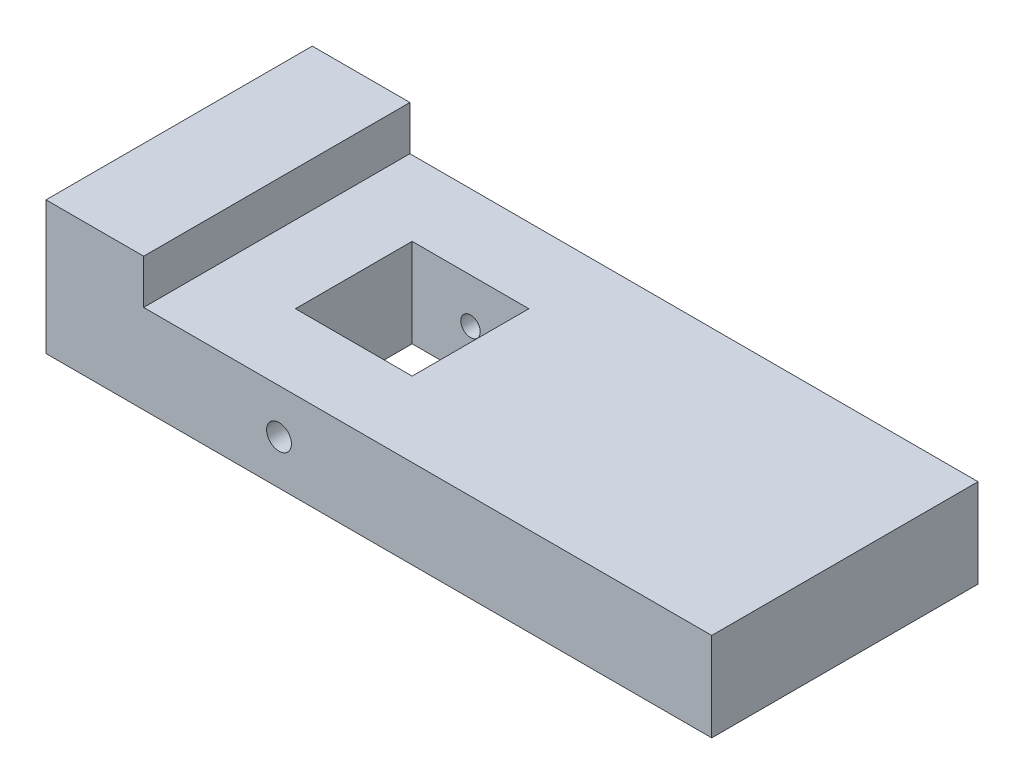
SolidWorks part; units mm, degrees
ref_plane "Front Plane" through (0, 0, 0) normal (0, 0, 1) x (1, 0, 0)
ref_plane "Top Plane" through (0, 0, 0) normal (0, 1, 0) x (1, 0, 0)
ref_plane "Right Plane" through (0, 0, 0) normal (1, 0, 0) x (0, 0, -1)
sketch "Sketch1" plane through (0, 0, 0) normal (0, 1, 0) x (1, 0, 0)
  line L1 (-75, -30) -> (75, -30)
  line L2 (-75, -30) -> (-75, 30)
  line L3 (-75, 30) -> (75, 30)
  line L4 (75, -30) -> (75, 30)
  line L5 (-75, -30) -> (75, 30) construction
  line L6 (-75, 30) -> (75, -30) construction
  point P0 (0, 0)
  dimension "D1" = 150
  dimension "D2" = 60
extrude "Boss-Extrude1" add sketch "Sketch1" along normal blind 20
sketch "Sketch2" plane through (0, 20, 0) normal (0, 1, 0) x (1, 0, 0)
  line L0 (-75, 30) -> (-75, -30) construction
  line L1 (-75, -30) -> (-53, -30)
  line L2 (-75, -30) -> (-75, 30)
  line L3 (-75, 30) -> (-53, 30)
  line L4 (-53, -30) -> (-53, 30)
  line L5 (-75, -30) -> (-53, 30) construction
  line L6 (-75, 30) -> (-53, -30) construction
  line L7 (75, 30) -> (-75, 30) construction
  point P0 (-64, 0)
  dimension "D1" = 22
  dimension "D2" = 60
  dimension "D3" = 0
  dimension "D4" = 0
extrude "Boss-Extrude2" add sketch "Sketch2" along normal blind 10
sketch "Sketch3" plane through (0, 20, 0) normal (0, 1, 0) x (1, 0, 0)
  line L0 (-53, -30) -> (75, -30) construction
  line L1 (-9.35, -13.15) -> (-35.65, -13.15)
  line L2 (-9.35, -13.15) -> (-9.35, 13.15)
  line L3 (-9.35, 13.15) -> (-35.65, 13.15)
  line L4 (-35.65, -13.15) -> (-35.65, 13.15)
  line L5 (-9.35, -13.15) -> (-35.65, 13.15) construction
  line L6 (-9.35, 13.15) -> (-35.65, -13.15) construction
  line L7 (-75, 30) -> (-75, -30) construction
  point P0 (-22.5, 0)
  dimension "D1" = 26.3
  dimension "D2" = 26.3
  dimension "D3" = 30
  dimension "D4" = 52.5
extrude "Cut-Extrude1" cut sketch "Sketch3" against normal through all
sketch "Sketch4" plane through (0, 0, 30) normal (0, 0, 1) x (1, 0, 0)
  line L0 (-75, 30) -> (-75, 0) construction
  line L1 (-75, 0) -> (75, 0) construction
  circle A0 centre (-22.5, 10) radius 2.2
  dimension "D1" = 4.4
  dimension "D2" = 52.5
  dimension "D3" = 10
extrude "Cut-Extrude2" cut sketch "Sketch4" against normal through all
sketch "Sketch5" plane through (0, 0, 30) normal (0, 0, 1) x (1, 0, 0)
  line L0 (-75, 30) -> (-75, 0) construction
  line L1 (-75, 0) -> (75, 0) construction
  circle A0 centre (-22.5, 10) radius 2.8
  dimension "D1" = 5.6
  dimension "D2" = 52.5
  dimension "D3" = 10
extrude "Cut-Extrude3" cut sketch "Sketch5" against normal blind 6
sketch "Sketch6" plane through (0, 0, 0) normal (0, -1, 0) x (-1, 0, 0)
  line L0 (75, 30) -> (75, -30) construction
  line L1 (-75, 30) -> (75, 30) construction
  circle A0 centre (0, 0) radius 4
  circle A1 centre (-55, 0) radius 4
  circle A2 centre (55, 0) radius 4
  dimension "D1" = 8
  dimension "D2" = 8
  dimension "D3" = 8
  dimension "D4" = 20
  dimension "D5" = 30
  dimension "D6" = 30
  dimension "D7" = 30
  dimension "D8" = 75
  dimension "D9" = 130
extrude "Cut-Extrude4" cut sketch "Sketch6" against normal blind 2
